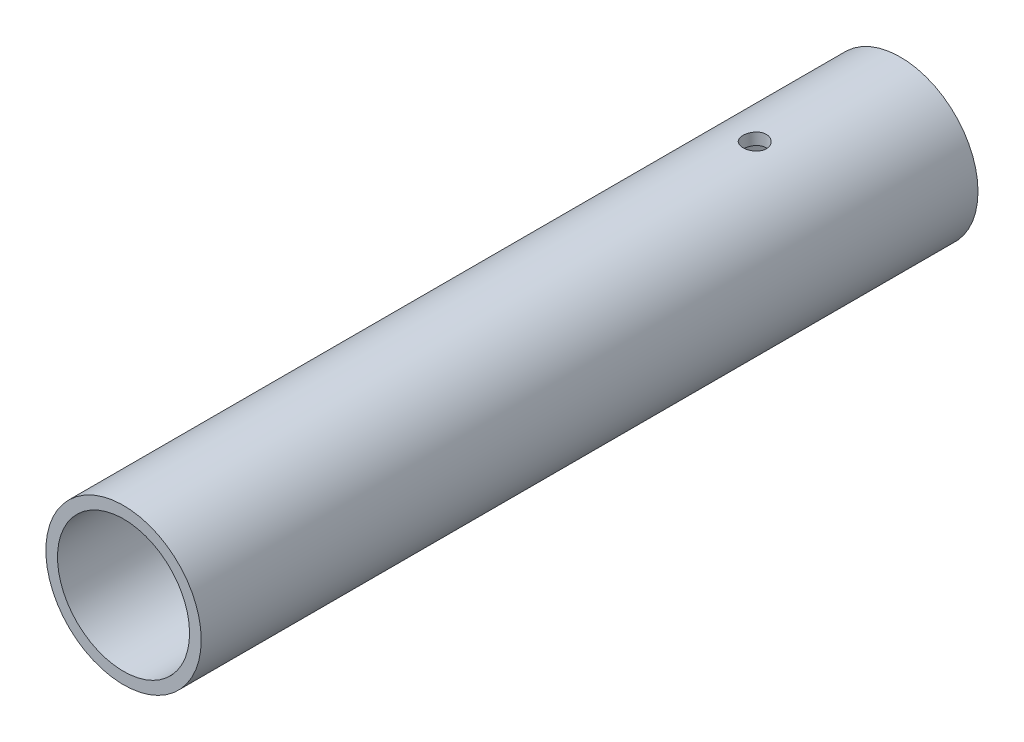
SolidWorks part; units mm, degrees
ref_plane "Front Plane" through (0, 0, 0) normal (0, 0, 1) x (1, 0, 0)
ref_plane "Top Plane" through (0, 0, 0) normal (0, 1, 0) x (1, 0, 0)
ref_plane "Right Plane" through (0, 0, 0) normal (1, 0, 0) x (0, 0, -1)
sketch "Sketch1" plane through (0, 0, 0) normal (0, 0, 1) x (1, 0, 0)
  circle A0 centre (0, 0) radius 20
  circle A1 centre (0, 0) radius 17
  dimension "D1" = 40
  dimension "D2" = 3
extrude "Boss-Extrude1" add sketch "Sketch1" along normal mid plane 200
sketch "Sketch2" plane through (0, 0, 0) normal (0, 1, 0) x (1, 0, 0)
  line L1 (20, 100) -> (-20, 100) construction
  circle A0 centre (0, 62.5) radius 3
  dimension "D2" = 6
  dimension "D1" = 37.5
extrude "Cut-Extrude1" cut sketch "Sketch2" against normal through all both and the other way through all
